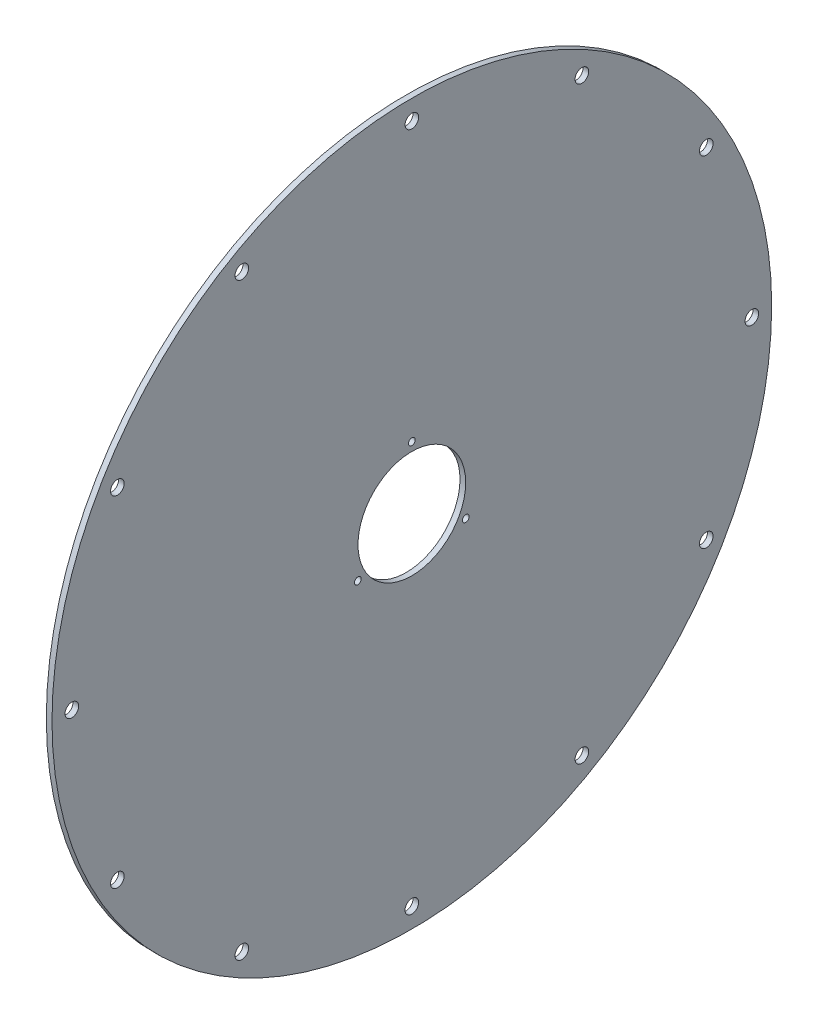
SolidWorks part; units mm, degrees
material "ASTM A36 Steel"
ref_plane "Front Plane" through (0, 0, 0) normal (0, 0, 1) x (1, 0, 0)
ref_plane "Top Plane" through (0, 0, 0) normal (0, 1, 0) x (1, 0, 0)
ref_plane "Right Plane" through (0, 0, 0) normal (1, 0, 0) x (0, 0, -1)
sketch "Sketch1" plane through (0, 0, 0) normal (1, 0, 0) x (0, 0, -1)
  circle A0 centre (0, 0) radius 317.5
  circle A1 centre (0, 0) radius 47.5
  dimension "D1" = 635
  dimension "D2" = 95
extrude "Boss-Extrude1" add sketch "Sketch1" along normal blind 5
sketch "Sketch2" plane through (5, 0, 0) normal (1, 0, 0) x (0, 0, -1)
  circle A1 centre (300, 0) radius 6
  circle A2 centre (0, 0) radius 47.5 construction
  dimension "D1" = 300
  dimension "D2" = 12
extrude "Cut-Extrude1" cut sketch "Sketch2" against normal blind 5
pattern_circular "CirPattern1" count 12 every 30 about axis through (0, 0, 0) along (1, 0, 0) of "Cut-Extrude1"
sketch "Sketch6" plane through (5, 0, 0) normal (1, 0, 0) x (0, 0, -1)
  circle A1 centre (0, 55) radius 3
  dimension "D2" = 6
extrude "Cut-Extrude2" cut sketch "Sketch6" against normal blind 10
pattern_circular "CirPattern2" count 3 over 360 about axis through (0, 0, 0) along (1, 0, 0) of "Cut-Extrude2"
